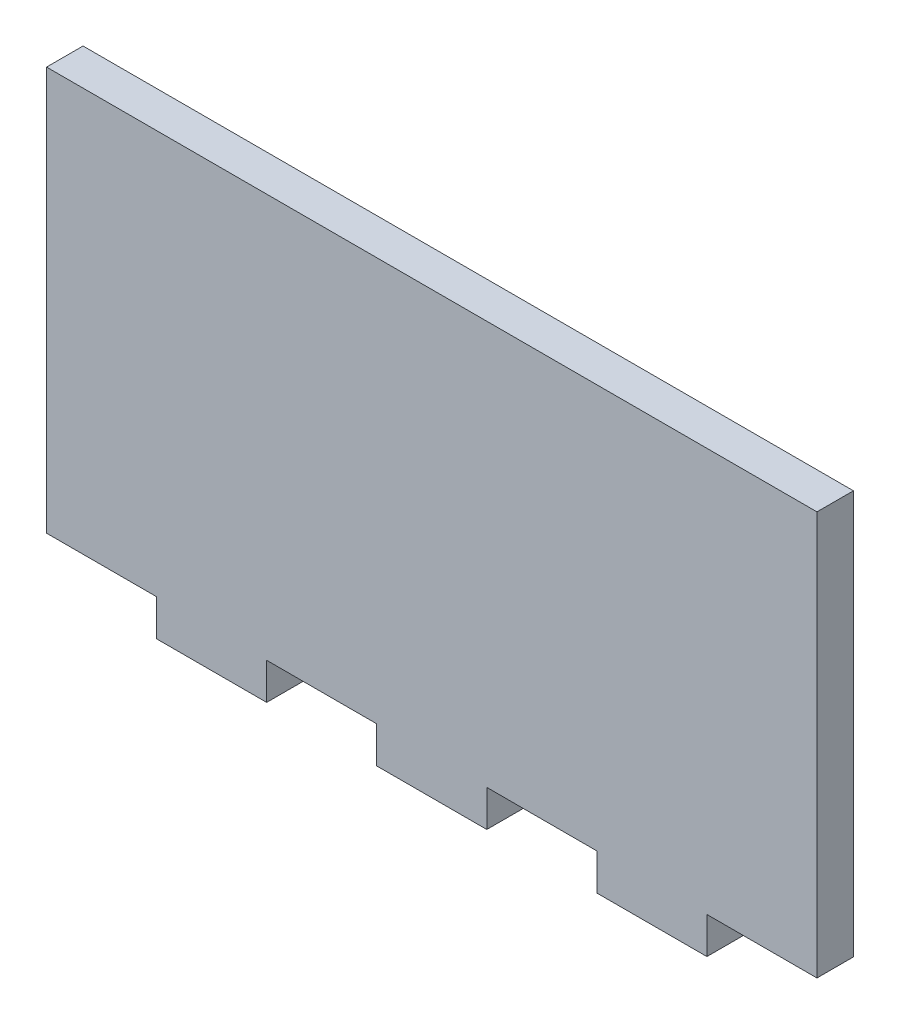
SolidWorks part; units mm, degrees
ref_plane "Front Plane" through (0, 0, 0) normal (0, 0, 1) x (1, 0, 0)
ref_plane "Top Plane" through (0, 0, 0) normal (0, 1, 0) x (1, 0, 0)
ref_plane "Right Plane" through (0, 0, 0) normal (1, 0, 0) x (0, 0, -1)
sketch "Sketch3" plane through (0, 0, 0) normal (0, 0, 1) x (1, 0, 0)
  line L1 (0, 0) -> (-67.056, 0)
  line L2 (0, 0) -> (0, 35.1384)
  line L3 (0, 35.1384) -> (-67.056, 35.1384)
  line L4 (-67.056, 0) -> (-67.056, 35.1384)
  dimension "D1" = 67.056
  dimension "D2" = 35.1384
extrude "Boss-Extrude1" add sketch "Sketch3" along normal blind 3.175
sketch "Sketch4" plane through (0, 0, 3.175) normal (0, 0, 1) x (1, 0, 0)
  line L0 (-57.4766, -3.175) -> (-57.4766, 0)
  line L1 (-67.056, 0) -> (-47.8971, 0)
  line L2 (-67.056, 0) -> (-67.056, -3.175)
  line L3 (-67.056, -3.175) -> (-47.8971, -3.175)
  line L4 (-47.8971, 0) -> (-47.8971, -3.175)
  line M8 (-67.056, 0) -> (0, 0)
  dimension "D1" = 19.1589
  dimension "D2" = 3.175
extrude "Boss-Extrude3" add sketch "Sketch4" against normal blind 3.175 contours L4 L0 L3 M8
pattern_linear "LPattern1" count 3 spacing 19.1589 along (1, 0, 0) of "Boss-Extrude3"
equation "\"chass_length\"= 12in"
equation "\"chass_width\"= 8in"
equation "\"hardboard_thickness\"= 0.125in"
equation "\"side_slot_length\"= \"chass_length\" / 27"
equation "\"motor_offset\"= 1.5in"
equation "\"motor_width\"= 1.3834in"
equation "\"motor_length\" = 2.64in"
equation "\"back_slot_length\"= \"chass_width\" / 17"
equation "\"motor_slot_length\"=\"motor_length\" / 7"
equation "\"D1@Sketch4\"=\"motor_slot_length\"*2"
equation "\"D2@Sketch4\"=\"hardboard_thickness\""
equation "\"D1@Boss-Extrude3\"=\"hardboard_thickness\""
equation "\"D1@LPattern1\"=\"motor_length\"/\"motor_slot_length\"*1/2-1"
equation "\"D3@LPattern1\"=\"motor_slot_length\"*2"
equation "\"D1@Sketch3\"=\"motor_length\""
equation "\"D2@Sketch3\"=\"motor_width\""
